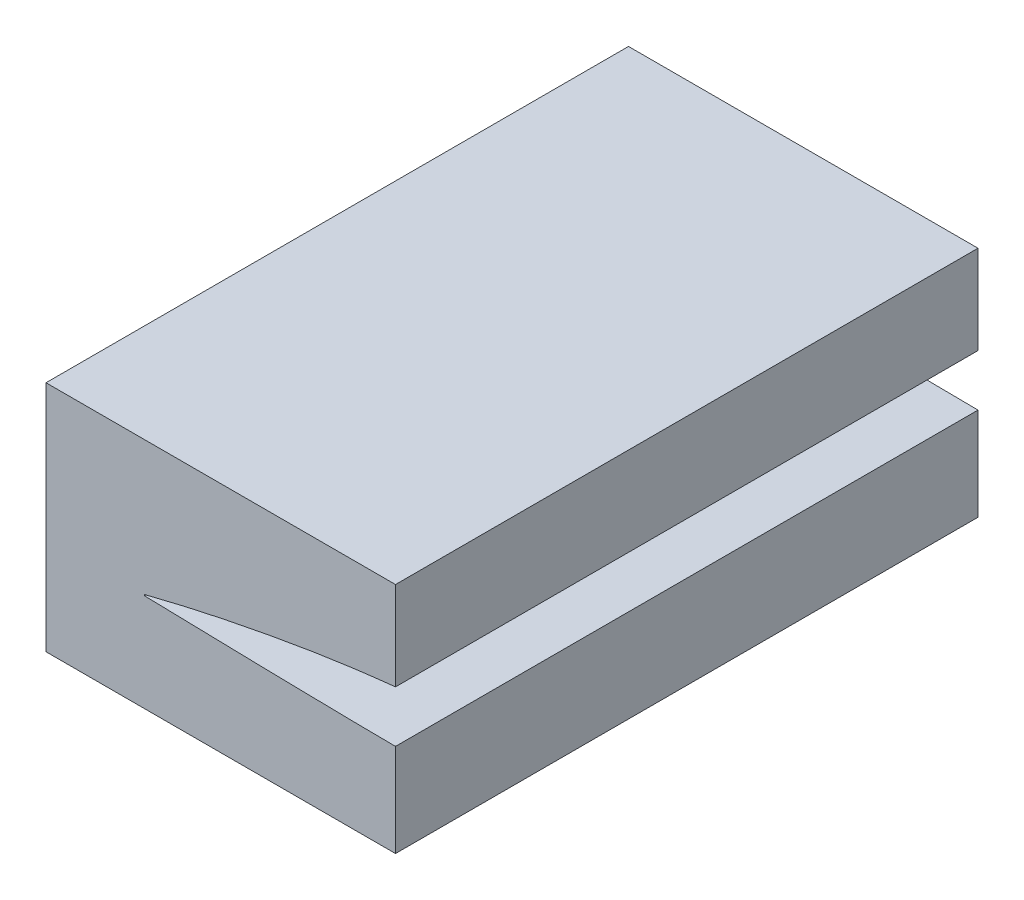
SolidWorks part; units mm, degrees
ref_plane "Front Plane" through (0, 0, 0) normal (0, 0, 1) x (1, 0, 0)
ref_plane "Top Plane" through (0, 0, 0) normal (0, 1, 0) x (1, 0, 0)
ref_plane "Right Plane" through (0, 0, 0) normal (1, 0, 0) x (0, 0, -1)
curve "Curve1"
  spline degree 3 poles (1, 0.0013, 0) (0.9833, 0.0047, 0) (0.9501, 0.0115, 0) (0.8835, 0.024, 0) (0.8002, 0.0379, 0) (0.7002, 0.0522, 0) (0.6002, 0.0641, 0) (0.5001, 0.0729, 0) (0.4001, 0.0788, 0) (0.3166, 0.0798, 0) (0.2499, 0.077, 0) (0.1999, 0.073, 0) (0.1498, 0.0666, 0) (0.108, 0.0587, 0) (0.0748, 0.0498, 0) (0.0496, 0.0416, 0) (0.0282, 0.0322, 0) (0.0098, 0.0207, 0) (-0.0063, 0.0009, 0) (0.0104, -0.0165, 0) (0.0285, -0.0245, 0) (0.0497, -0.0305, 0) (0.0749, -0.0348, 0) (0.1083, -0.0385, 0) (0.1499, -0.0414, 0) (0.2, -0.0425, 0) (0.25, -0.0424, 0) (0.3167, -0.0409, 0) (0.4, -0.0382, 0) (0.5, -0.0336, 0) (0.6, -0.0276, 0) (0.7, -0.0214, 0) (0.8, -0.0151, 0) (0.8833, -0.0093, 0) (0.95, -0.0048, 0) (0.9833, -0.0025, 0) (1, -0.0013, 0) knots 0 0 0 0 0.025012 0.049959 0.099673 0.149206 0.198581 0.247805 0.296917 0.345953 0.370492 0.395091 0.419815 0.444799 0.45749 0.470406 0.483879 0.491264 0.503459 0.513609 0.520451 0.533235 0.545691 0.558032 0.582609 0.607135 0.631652 0.656174 0.705234 0.75432 0.803437 0.852566 0.901701 0.950849 0.975423 1 1 1 1
sketch "Sketch2" plane through (17.4402, 0, 0) normal (0, 0, 1) x (1, 0, 0)
  line L0 (-17.4402, 5.3904) -> (-17.4402, 13)
  line L1 (-17.4402, 0.9686) -> (-17.4402, -7)
  line L2 (-47.4402, 13) -> (-17.4402, 13)
  line L3 (-47.4402, 13) -> (-47.4402, -7)
  line L4 (-47.4402, -7) -> (-17.4402, -7)
  arc A1 (-38.9552, 1.4929) -> (-38.9506, 1.389) centre (-38.942, 1.4414) ccw
  spline S0 degree 3 poles (-38.9552, 1.4929) (-38.2955, 1.6584) (-36.9778, 1.9889) (-34.3381, 2.6041) (-31.0337, 3.3023) (-27.0617, 4.0491) (-23.0862, 4.7008) (-19.8763, 5.1232) (-17.9933, 5.3329) (-17.4402, 5.3904) knots 0 0 0 0 0.025012 0.049959 0.099673 0.149206 0.198581 0.247805 0.268255 0.268255 0.268255 0.268255
  spline S1 degree 3 poles (-17.4402, 0.9686) (-17.9313, 0.9707) (-19.7581, 0.9831) (-22.9203, 1.0343) (-26.9271, 1.1087) (-30.9348, 1.1861) (-34.2744, 1.2726) (-36.9465, 1.3352) (-38.2826, 1.3711) (-38.9506, 1.389) knots 0.736257 0.736257 0.736257 0.736257 0.75432 0.803437 0.852566 0.901701 0.950849 0.975423 1 1 1 1
  dimension "D4" = 20
extrude "Boss-Extrude1" add sketch "Sketch2" along normal blind 50 contours L2 L0 S0 A1 S1 L1 L4 L3
